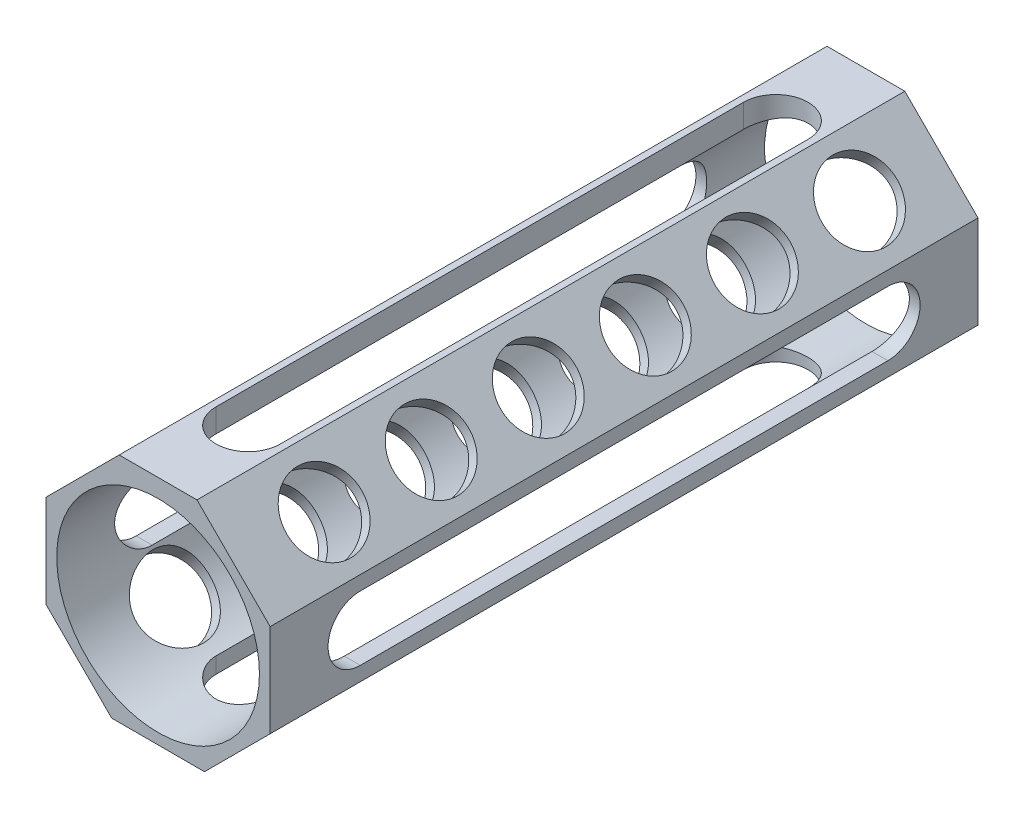
SolidWorks part; units mm, degrees
ref_plane "Ebene vorne" through (0, 0, 0) normal (1, 0, 0) x (0, 1, 0)
ref_plane "Ebene oben" through (0, 0, 0) normal (0, 0, 1) x (0, 1, 0)
ref_plane "Ebene rechts" through (0, 0, 0) normal (0, 1, 0) x (-1, 0, 0)
sketch "Skizze1" plane through (0, 0, 0) normal (0, 0, 1) x (0, 1, 0)
  line L0 (11.1508, 3.6277) -> (11.1508, -3.6277)
  line L13 (11.1508, 3.6277) -> (4.3285, 10.45)
  line L14 (4.3285, 10.45) -> (-4.3285, 10.45)
  line L15 (-4.3285, 10.45) -> (-10.45, 4.3285)
  line L16 (-10.45, 4.3285) -> (-10.45, -4.3285)
  line L17 (-10.45, -4.3285) -> (-4.3285, -10.45)
  line L18 (-4.3285, -10.45) -> (4.3285, -10.45)
  line L19 (4.3285, -10.45) -> (11.1508, -3.6277)
  line L29 (10.45, -2.605) -> (10.45, 5.6378) [skipped]
  circle A0 centre (0, 0) radius 9.45
  circle A1 centre (0, 0) radius 10.45 construction
  dimension "D1" = 18.9
  dimension "D2" = 20.9
extrude "Aufsatz-Linear austragen1" add sketch "Skizze1" along normal blind 66
sketch "Skizze9" plane through (7.3893, 7.3893, 0) normal (0.7071, 0.7071, 0) x (-0.7071, 0.7071, 0)
  line L0 (0.4955, 66) -> (0, 0) construction
  line L1 (-4.3285, 66) -> (5.3196, 66) construction
  circle A0 centre (0.4325, 57.6) radius 3.5
  circle A1 centre (0.4566, 47.6) radius 3.5
  circle A2 centre (0.4807, 37.6001) radius 3.5
  circle A3 centre (0.5048, 27.6001) radius 3.5
  circle A4 centre (0.5289, 17.6001) radius 3.5
  circle A5 centre (0.553, 7.6001) radius 3.5
  dimension "D1" = 7
  dimension "D2" = 8.4
  dimension "D3" = 6
extrude "Schnitt-Linear austragen8" cut sketch "Skizze9" against normal through all
sketch "Skizze10" plane through (0, 11.1508, 0) normal (0, 1, 0) x (-1, 0, 0)
  line L0 (0, 66) -> (0, 0) construction
  line L1 (-3.6277, 66) -> (3.6277, 66) construction
  line L2 (0, 8.4) -> (0, 57.6) construction
  line L3 (-3, 8.4) -> (-3, 57.6)
  line L4 (3, 8.4) -> (3, 57.6)
  arc A0 (-3, 8.4) -> (3, 8.4) centre (0, 8.4) ccw
  arc A1 (3, 57.6) -> (-3, 57.6) centre (0, 57.6) ccw
  point P7 (0, 33)
  dimension "D2" = 3
  dimension "D1" = 8.4
extrude "Schnitt-Linear austragen9" cut sketch "Skizze10" against normal through all
sketch "Skizze11" plane through (10.45, 0, 0) normal (1, 0, 0) x (0, 1, 0)
  line L0 (0, 66) -> (0, 0) construction
  line L1 (-4.3285, 66) -> (4.3285, 66) construction
  line L2 (0, 8.4) -> (0, 57.6) construction
  line L3 (-3, 8.4) -> (-3, 57.6)
  line L4 (3, 8.4) -> (3, 57.6)
  arc A0 (-3, 8.4) -> (3, 8.4) centre (0, 8.4) ccw
  arc A1 (3, 57.6) -> (-3, 57.6) centre (0, 57.6) ccw
  point P7 (0, 33)
  dimension "D1" = 3
  dimension "D2" = 8.4
extrude "Schnitt-Linear austragen10" cut sketch "Skizze11" against normal through all
sketch "Skizze12" plane through (7.3893, -7.3893, 0) normal (0.7071, -0.7071, 0) x (0.7071, 0.7071, 0)
  line L0 (0, 66) -> (0, 0) construction
  line L1 (-4.3285, 66) -> (4.3285, 66) construction
  line L2 (0, 8.4) -> (0, 57.6) construction
  line L3 (-3, 8.4) -> (-3, 57.6)
  line L4 (3, 8.4) -> (3, 57.6)
  arc A0 (-3, 8.4) -> (3, 8.4) centre (0, 8.4) ccw
  arc A1 (3, 57.6) -> (-3, 57.6) centre (0, 57.6) ccw
  point P7 (0, 33)
  dimension "D2" = 3
  dimension "D1" = 8.4
extrude "Schnitt-Linear austragen11" cut sketch "Skizze12" against normal through all
